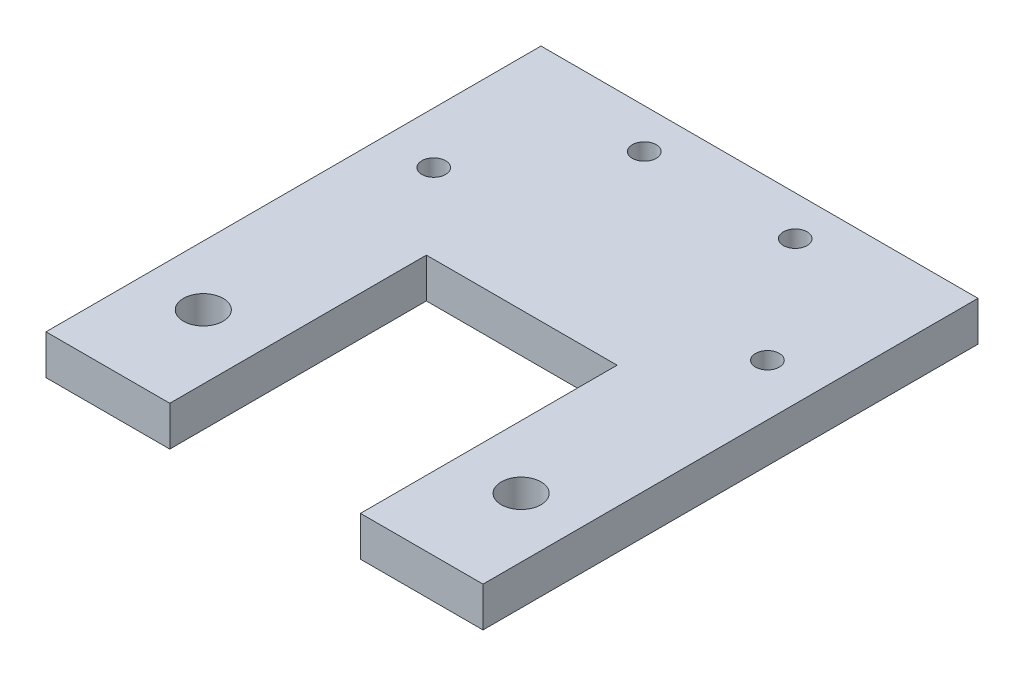
SolidWorks part; units mm, degrees
ref_plane "Front Plane" through (0, 0, 0) normal (0, 0, 1) x (1, 0, 0)
ref_plane "Top Plane" through (0, 0, 0) normal (0, 1, 0) x (1, 0, 0)
ref_plane "Right Plane" through (0, 0, 0) normal (1, 0, 0) x (0, 0, -1)
sketch "Sketch1" plane through (0, 0, 0) normal (0, 1, 0) x (1, 0, 0)
  line L1 (-32.5, 50) -> (32.5, 50)
  line L2 (-32.5, 50) -> (-32.5, -50)
  line L3 (-32.5, -50) -> (32.5, -50)
  line L4 (32.5, 50) -> (32.5, -50)
  line L5 (-32.5, 50) -> (32.5, -50) construction
  line L6 (-32.5, -50) -> (32.5, 50) construction
  point P1 (0, 0)
  dimension "D1" = 100
  dimension "D2" = 65
extrude "Boss-Extrude1" add sketch "Sketch1" along normal blind 5
sketch "Sketch3" plane through (0, 5, 0) normal (0, 1, 0) x (1, 0, 0)
  circle A0 centre (-21, 30) radius 1.5
  circle A1 centre (21, 30) radius 1.5
  circle A2 centre (-9.5, 45) radius 1.5
  circle A3 centre (9.5, 45) radius 1.5
  circle A4 centre (-20, 0) radius 2.5
  circle A5 centre (20, 0) radius 2.5
extrude "Cut-Extrude2" cut sketch "Sketch3" against normal blind 5
sketch "Sketch4" plane through (0, 5, 0) normal (0, 1, 0) x (1, 0, 0)
sketch "Sketch5" plane through (0, 5, 0) normal (0, 1, 0) x (1, 0, 0)
  line L0 (-32.5, -50) -> (32.5, -50) construction
  line L1 (-11.9235, 20) -> (12.0765, 20)
  line L2 (-11.9235, 20) -> (-11.9235, -50)
  line L3 (-11.9235, -50) -> (12.0765, -50)
  line L4 (12.0765, 20) -> (12.0765, -50)
  line L5 (-11.9235, 20) -> (12.0765, -50) construction
  line L6 (-11.9235, -50) -> (12.0765, 20) construction
  point P0 (0.0765, -15)
  dimension "D1" = 70
  dimension "D2" = 24
extrude "Cut-Extrude4" cut sketch "Sketch5" against normal blind 5
sketch "Sketch6" plane through (0, 5, 0) normal (0, 1, 0) x (1, 0, 0)
  line L0 (-32.5, -40) -> (32.5, -40)
  line L1 (-32.5, 50) -> (-32.5, -50) construction
  line L2 (32.5, -50) -> (32.5, 50) construction
  line L3 (32.5, -40) -> (32.5, -50)
  line L4 (32.5, -50) -> (-32.5, -50)
  line L5 (-32.5, -50) -> (-32.5, -40)
  dimension "D1" = 10
extrude "Cut-Extrude5" cut sketch "Sketch6" against normal blind 5
sketch "Sketch7" plane through (0, 5, 0) normal (0, 1, 0) x (1, 0, 0)
  line L0 (-32.5, -12.296) -> (-11.9235, -12.296)
  line L1 (-32.5, 50) -> (-32.5, -40) construction
  line L2 (-11.9235, 20) -> (-11.9235, -40) construction
  line L3 (-11.9235, -12.296) -> (-11.9235, -40)
  line L4 (-11.9235, -40) -> (-32.5, -40)
  line L5 (-32.5, -40) -> (-32.5, -12.296)
extrude "Cut-Extrude6" cut sketch "Sketch7" against normal blind 5
sketch "Sketch8" plane through (0, 5, 0) normal (0, 1, 0) x (1, 0, 0)
  line L0 (12.0765, -12.296) -> (32.5, -12.296)
  line L1 (12.0765, -40) -> (12.0765, 20) construction
  line L2 (32.5, -40) -> (32.5, 50) construction
  line L3 (32.5, -12.296) -> (32.5, -40)
  line L4 (32.5, -40) -> (12.0765, -40)
  line L5 (12.0765, -40) -> (12.0765, -12.296)
extrude "Cut-Extrude7" cut sketch "Sketch8" against normal blind 5
sketch "Sketch9" plane through (0, 5, 0) normal (0, 1, 0) x (1, 0, 0)
  line L0 (-27.5, 50) -> (-27.5, -12.296)
  line L1 (32.5, 50) -> (-32.5, 50) construction
  line L2 (-11.9235, -12.296) -> (-32.5, -12.296) construction
  line L3 (-27.5, 34.8013) -> (-27.5, 18.852)
  line L5 (-32.5, 50) -> (-32.5, -12.296) construction
  line L6 (-27.5, 50) -> (-32.5, 50)
  line L7 (-32.5, 50) -> (-32.5, -12.296)
  line L8 (-32.5, -12.296) -> (-27.5, -12.296)
  line M4 (32.5, 50) -> (-32.5, 50)
  line M5 (-32.5, 50) -> (-32.5, -12.296)
  line M6 (-32.5, -12.296) -> (-11.9235, -12.296)
extrude "Cut-Extrude8" cut sketch "Sketch9" against normal blind 5 contours L0 M4 M5 M6
sketch "Sketch10" plane through (0, 5, 0) normal (0, 1, 0) x (1, 0, 0)
  line L0 (27.5, 50) -> (27.5, -12.296)
  line L1 (32.5, 50) -> (-27.5, 50) construction
  line L2 (32.5, -12.296) -> (12.0765, -12.296) construction
  line L3 (27.5, -12.296) -> (32.5, -12.296)
  line L4 (32.5, -12.296) -> (32.5, 50)
  line L5 (32.5, 50) -> (27.5, 50)
extrude "Cut-Extrude9" cut sketch "Sketch10" against normal blind 5 contours L5 L0 L3 L4
